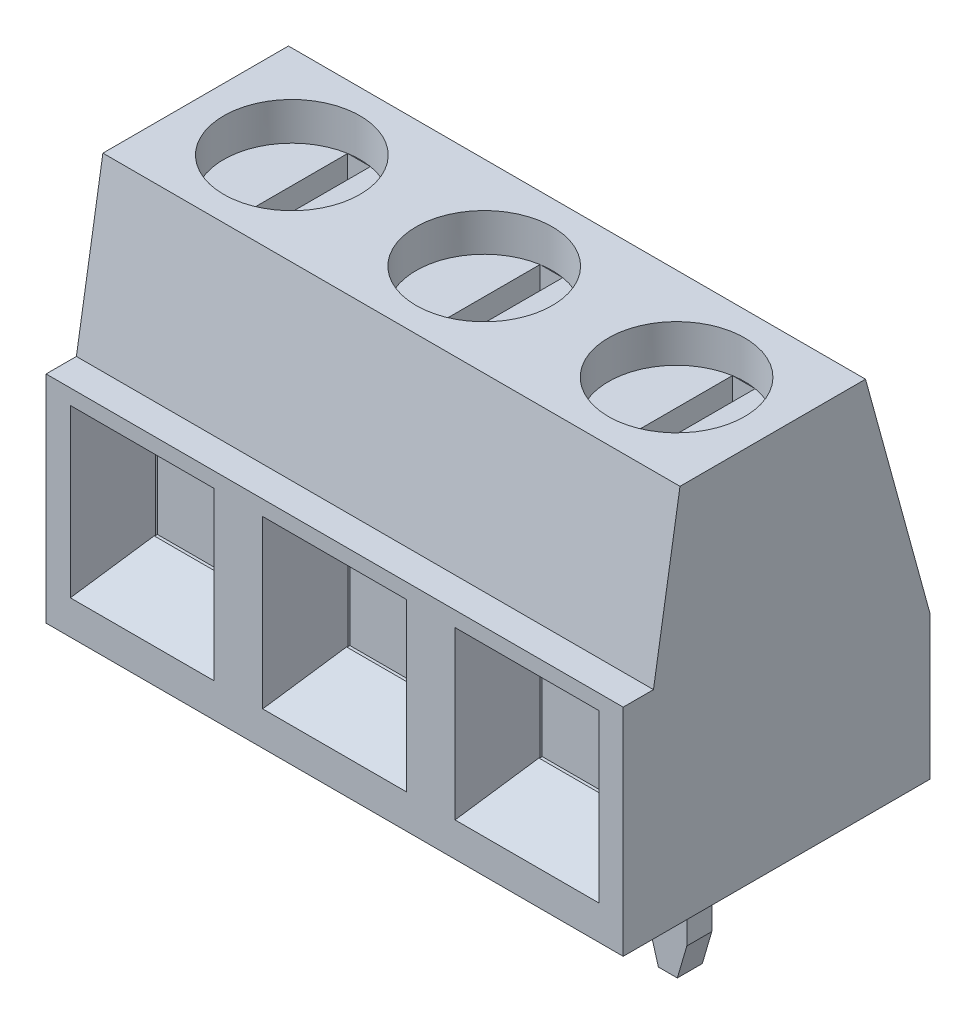
SolidWorks part; units mm, degrees
ref_plane "Front Plane" through (0, 0, 0) normal (0, 0, 1) x (1, 0, 0)
ref_plane "Top Plane" through (0, 0, 0) normal (0, 1, 0) x (1, 0, 0)
ref_plane "Right Plane" through (0, 0, 0) normal (1, 0, 0) x (0, 0, -1)
sketch "Sketch1" plane through (0, 0, 0) normal (0, 1, 0) x (1, 0, 0)
  line L1 (0, 0) -> (15.24, 0)
  line L2 (0, 0) -> (0, 8.1)
  line L3 (0, 8.1) -> (15.24, 8.1)
  line L4 (15.24, 0) -> (15.24, 8.1)
  dimension "D1" = 8.1
  dimension "D2" = 15.24
extrude "Boss-Extrude1" add sketch "Sketch1" along normal blind 10
sketch "Sketch2" plane through (15.24, 0, 0) normal (1, 0, 0) x (0, 0, -1)
  line L0 (0, 10) -> (1.5, 10)
  line L1 (0, 10) -> (8.1, 10) construction
  line L4 (0, 5.7) -> (0, 10)
  line L5 (0, 5.7) -> (0.8, 5.7)
  line L6 (0.8, 5.7) -> (1.5, 10)
  dimension "D1" = 1.5
  dimension "D2" = 0.8
  dimension "D3" = 4.3
extrude "Cut-Extrude1" cut sketch "Sketch2" against normal through all
sketch "Sketch3" plane through (15.24, 0, 0) normal (1, 0, 0) x (0, 0, -1)
  line L0 (8.1, 3.8) -> (6.4, 10)
  line L1 (8.1, 10) -> (8.1, 0) construction
  line L2 (1.5, 10) -> (8.1, 10) construction
  line L3 (6.4, 10) -> (8.1, 10)
  line L4 (8.1, 10) -> (8.1, 3.8)
  dimension "D1" = 1.7
  dimension "D2" = 6.2
extrude "Cut-Extrude2" cut sketch "Sketch3" against normal through all
sketch "Sketch4" plane through (0, 0, 0) normal (0, -1, 0) x (1, 0, 0)
  line L0 (0, -4.05) -> (2.54, -4.05) construction
  line L1 (0, -8.1) -> (0, 0) construction
  line L3 (3.04, -3.72) -> (2.04, -3.72)
  line L4 (3.04, -3.72) -> (3.04, -4.38)
  line L6 (3.04, -4.38) -> (2.04, -4.38)
  line L7 (2.04, -3.72) -> (2.04, -4.38)
  line L8 (3.04, -3.72) -> (2.04, -4.38) construction
  line L9 (3.04, -4.38) -> (2.04, -3.72) construction
  dimension "D1" = 2.54
  dimension "D2" = 1
  dimension "D3" = 0.66
extrude "Boss-Extrude2" add sketch "Sketch4" along normal blind 3.5
sketch "Sketch5" plane through (0, 0, -3.72) normal (0, 0, 1) x (1, 0, 0)
  line L0 (2.04, -2.6434) -> (2.29, -3.5)
  line L1 (2.04, -3.5) -> (2.04, 0) construction
  line L2 (3.04, -3.5) -> (2.04, -3.5) construction
  line L3 (2.29, -3.5) -> (2.04, -3.5)
  line L4 (2.04, -3.5) -> (2.04, -2.6434)
  line L5 (2.04, -2.6434) -> (3.04, -2.6434) construction
  line L6 (3.04, -3.5) -> (3.04, 0) construction
  line L7 (2.29, -3.5) -> (2.79, -3.5) construction
  line L8 (2.79, -3.5) -> (3.04, -3.5)
  line L9 (3.04, -3.5) -> (3.04, -2.6434)
  line L10 (3.04, -2.6434) -> (2.79, -3.5)
  dimension "D1" = 0.5
extrude "Cut-Extrude3" cut sketch "Sketch5" against normal up to next
pattern_linear "LPattern1" count 3 spacing 5.08 along (1, 0, 0) of "Boss-Extrude2", "Cut-Extrude3"
sketch "Sketch6" plane through (0, 0, 0) normal (0, 0, 1) x (1, 0, 0)
  line L0 (2.54, 2.75) -> (0, 2.75) construction
  line L1 (1.24, 1.8) -> (3.84, 1.8)
  line L2 (1.24, 1.8) -> (1.24, 3.7)
  line L3 (1.24, 3.7) -> (3.84, 3.7)
  line L4 (3.84, 1.8) -> (3.84, 3.7)
  line L5 (1.24, 1.8) -> (3.84, 3.7) construction
  line L6 (1.24, 3.7) -> (3.84, 1.8) construction
  line L7 (0, 5.7) -> (0, 0) construction
  line L8 (2.54, 1.8) -> (2.54, 0) construction
  line L9 (0, 0) -> (15.24, 0) construction
  point P0 (2.54, 2.75)
  dimension "D1" = 1.8
  dimension "D2" = 2.54
  dimension "D3" = 1.9
  dimension "D4" = 2.6
extrude "Cut-Extrude4" cut sketch "Sketch6" against normal blind 1.7
chamfer "Chamfer1" distance 0.6 angle 70 1 edges at (1.24, 2.75, 0)
chamfer "Chamfer2" distance 0.6 angle 70 1 edges at (3.84, 2.75, 0)
chamfer "Chamfer3" distance 1.6 angle 45 1 edges at (2.54, 3.7, 0)
chamfer "Chamfer4" distance 0.9 angle 61 1 edges at (2.54, 1.8, 0)
pattern_linear "LPattern2" count 3 spacing 5.08 along (1, 0, 0) of "Chamfer4", "Chamfer3", "Chamfer2", "Chamfer1", "Cut-Extrude4"
sketch "Sketch7" plane through (0, 10, 0) normal (0, 1, 0) x (1, 0, 0)
  line L0 (15.24, 3.95) -> (12.7, 3.95) construction
  line L1 (15.24, 1.5) -> (15.24, 6.4) construction
  circle A0 centre (12.7, 3.95) radius 1.8
  dimension "D2" = 3.6
  dimension "D1" = 2.54
extrude "Cut-Extrude5" cut sketch "Sketch7" against normal blind 1
sketch "Sketch8" plane through (0, 9, 0) normal (0, 1, 0) x (1, 0, 0)
  line L0 (12.7, 2.15) -> (12.7, 5.75) construction
  line L2 (12.4, 2.1752) -> (13, 2.1752)
  line L3 (12.4, 2.1752) -> (12.4, 5.7248)
  line L4 (12.4, 5.7248) -> (13, 5.7248)
  line L5 (13, 2.1752) -> (13, 5.7248)
  line L6 (12.4, 2.1752) -> (13, 5.7248) construction
  line L7 (12.4, 5.7248) -> (13, 2.1752) construction
  circle A0 centre (12.7, 3.95) radius 1.8 construction
  point P5 (12.7, 3.95)
  point P10 (12.4, 5.7248)
  dimension "D1" = 0.6
extrude "Cut-Extrude6" cut sketch "Sketch8" against normal blind 1
pattern_linear "LPattern3" count 3 spacing 5.08 along (-1, 0, 0) of "Cut-Extrude5", "Cut-Extrude6"
